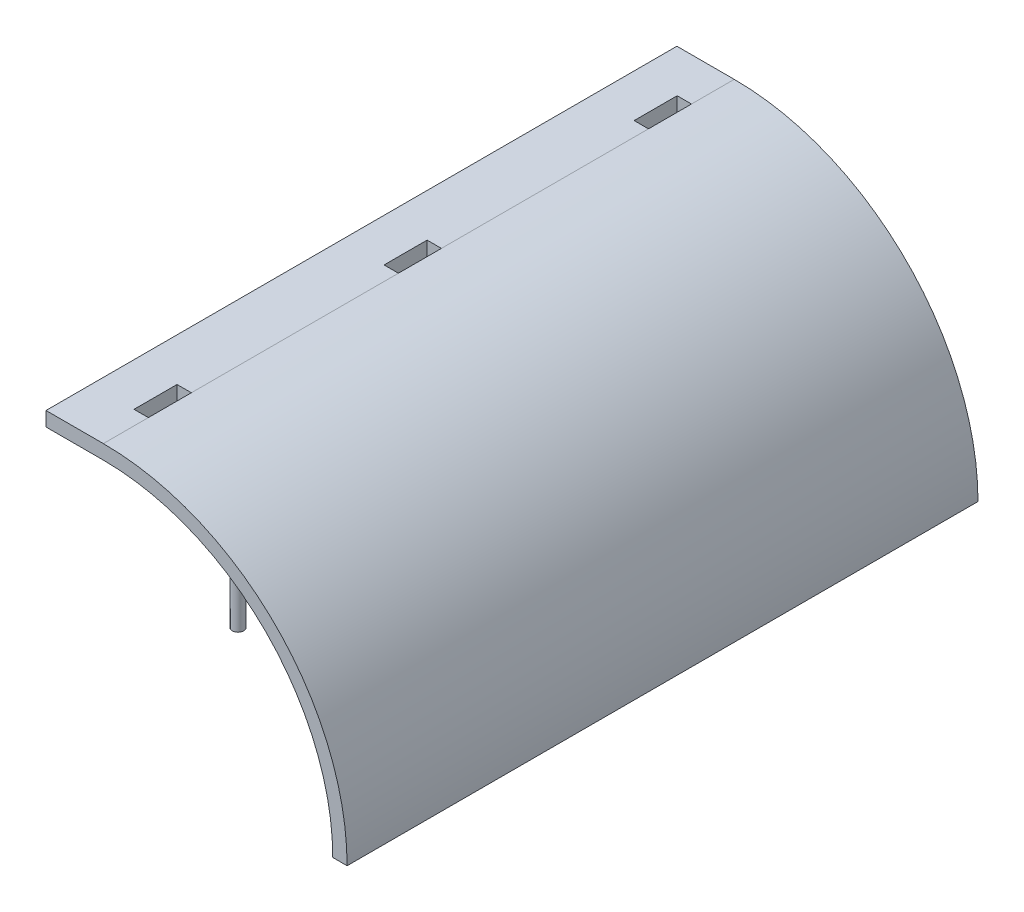
SolidWorks part; units mm, degrees
ref_plane "Front Plane" through (0, 0, 0) normal (0, 0, 1) x (1, 0, 0)
ref_plane "Top Plane" through (0, 0, 0) normal (0, 1, 0) x (1, 0, 0)
ref_plane "Right Plane" through (0, 0, 0) normal (1, 0, 0) x (0, 0, -1)
sketch "Sketch2" plane through (0, 0, 0) normal (0, 0, 1) x (1, 0, 0)
  line L0 (-50.8, 50.8) -> (-50.8, 0) construction
  line L1 (-50.8, 0) -> (0, 0) construction
  line L2 (-50.8, 50.8) -> (-60.325, 50.8)
  line L3 (-50.8, 53.975) -> (-60.325, 53.975)
  line L4 (-60.325, 50.8) -> (-60.325, 53.975)
  line L5 (3.175, 0) -> (0, 0)
  arc A0 (0, 0) -> (-50.8, 50.8) centre (-50.8, 0) ccw
  arc A1 (3.175, 0) -> (-50.8, 53.975) centre (-50.8, 0) ccw
  dimension "D1" = 50.8
  dimension "D2" = 9.525
  dimension "D3" = 3.175
extrude "Boss-Extrude1" add sketch "Sketch2" along normal blind 139.7
sketch "Sketch3" plane through (-60.325, 0, 0) normal (-1, 0, 0) x (0, 0, 1)
  line L0 (139.7, 53.975) -> (0, 53.975) construction
  line L1 (0, 53.975) -> (139.7, 53.975)
  line L2 (0, 53.975) -> (0, 50.8)
  line L3 (0, 50.8) -> (139.7, 50.8)
  line L4 (139.7, 53.975) -> (139.7, 50.8)
  line L5 (0, 53.975) -> (0, 50.8) construction
  line L6 (139.7, 50.8) -> (0, 50.8) construction
extrude "Boss-Extrude2" add sketch "Sketch3" along normal blind 3.175
sketch "Sketch4" plane through (0, 50.8, 0) normal (0, -1, 0) x (1, 0, 0)
  line L0 (-50.8, 139.7) -> (-50.8, 0) construction
  line L1 (-53.975, 129.7342) -> (-50.8, 129.7342)
  line L2 (-53.975, 129.7342) -> (-53.975, 120.2092)
  line L3 (-53.975, 120.2092) -> (-50.8, 120.2092)
  line L4 (-50.8, 129.7342) -> (-50.8, 120.2092)
  dimension "D1" = 9.525
extrude "Cut-Extrude1" cut sketch "Sketch4" against normal through all
pattern_linear "LPattern1" count 3 spacing 55.372 along (0, 0, -1) of "Cut-Extrude1"
sketch "Sketch5" plane through (0, 53.975, 0) normal (0, 1, 0) x (1, 0, 0)
  line L1 (-50.8, -9.4652) -> (-50.8, 0) construction
  line L3 (3.175, 0) -> (-50.8, 0) construction
  line L4 (-50.8, -69.5997) -> (3.175, -69.85) construction
  line L5 (-50.8, -64.8372) -> (-50.8, -74.3622) construction
  line L6 (3.175, -139.7) -> (3.175, 0) construction
  circle A0 centre (-25.4, -4.7625) radius 1.27
  circle A1 centre (-26.0024, -134.6697) radius 1.27
  dimension "D3" = 2.54
  dimension "D1" = 25.4
  dimension "D2" = 4.7625
extrude "Boss-Extrude3" add sketch "Sketch5" against normal blind 25.4
sketch "Sketch6" plane through (0, 0, 139.7) normal (0, 0, 1) x (1, 0, 0)
  arc A0 (-50.8, 53.975) -> (3.175, 0) centre (-50.8, 0) cw
  arc A1 (3.175, 0) -> (-50.8, 53.975) centre (-50.8, 0) ccw construction
  arc A2 (-50.8, 53.975) -> (3.175, 0) centre (-17.429, 33.371) cw
extrude "Cut-Extrude2" cut sketch "Sketch6" against normal through all
